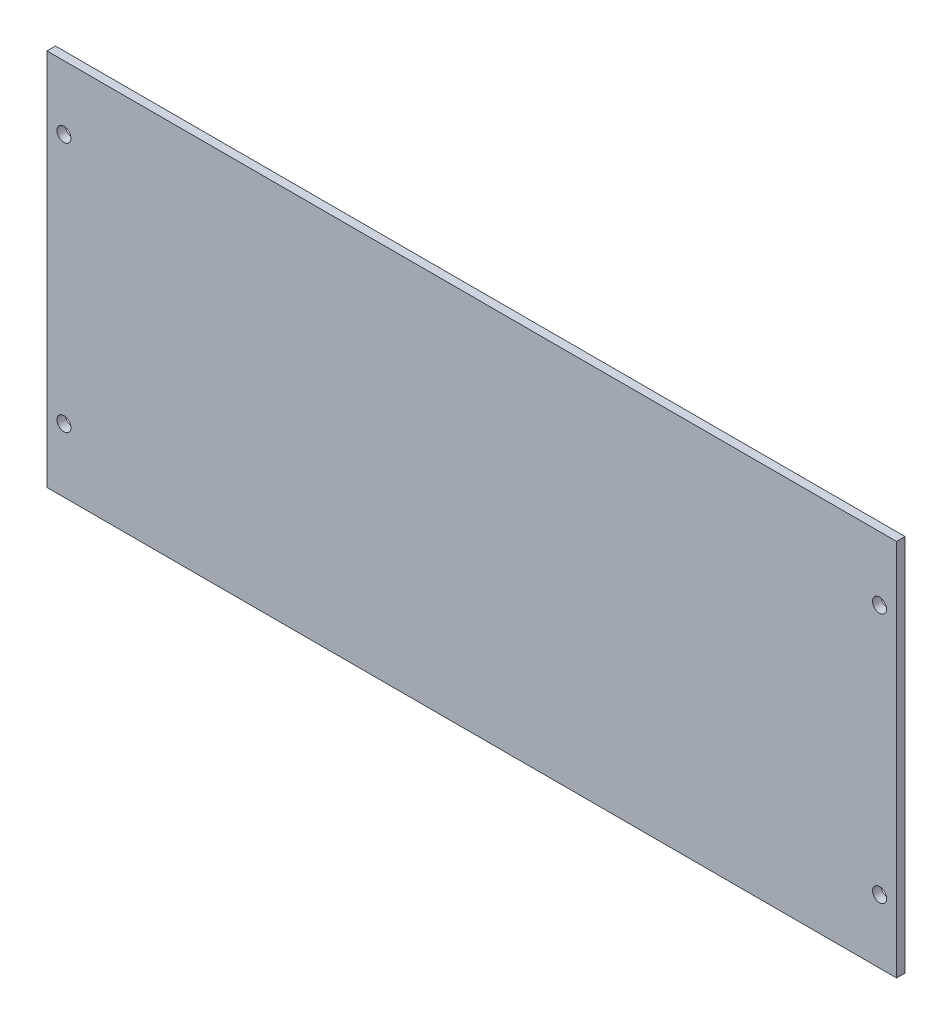
SolidWorks part; units mm, degrees
ref_plane "Plan de face" through (0, 0, 0) normal (0, 0, 1) x (1, 0, 0)
ref_plane "Plan de dessus" through (0, 0, 0) normal (0, 1, 0) x (1, 0, 0)
ref_plane "Plan de droite" through (0, 0, 0) normal (1, 0, 0) x (0, 0, -1)
sketch "Esquisse1" plane through (0, 0, 0) normal (0, 0, 1) x (1, 0, 0)
  line L1 (-200, -89) -> (200, -89)
  line L2 (-200, -89) -> (-200, 89)
  line L3 (-200, 89) -> (200, 89)
  line L4 (200, -89) -> (200, 89)
  line L5 (-200, -89) -> (200, 89) construction
  line L6 (-200, 89) -> (200, -89) construction
  point P0 (0, 0)
  dimension "D1" = 178
  dimension "D2" = 400
extrude "Boss.-Extru.1" add sketch "Esquisse1" along normal blind 4
sketch "Esquisse2" plane through (0, 0, 0) normal (0, 0, -1) x (-1, 0, 0)
  line L0 (200, -89) -> (-200, -89) construction
  line L1 (192, -81) -> (-192, -81) construction
  line L2 (192, -81) -> (192, 81) construction
  line L3 (192, 81) -> (-192, 81) construction
  line L4 (-192, -81) -> (-192, 81) construction
  line L5 (192, -81) -> (-192, 81) construction
  line L6 (192, 81) -> (-192, -81) construction
  line L7 (-200, -89) -> (-200, 89) construction
  line L8 (-153.9304, 0) -> (204.6118, 0) construction
  line L9 (0, -141.2759) -> (0, 199.6584) construction
  point P0 (0, 0)
  point P14 (-192, -59)
  point P15 (-192, 59)
  point P16 (192, -59)
  point P17 (192, 59)
  point P18 (0, 81)
  dimension "D1" = 8
  dimension "D2" = 8
  dimension "D3" = 30
hole_wizard "Dégagement M61" positions "Esquisse3D1" profile "Esquisse3" hole size "M6" standard "ISO" end condition through all
sketch3d "Esquisse3D1"
  point P3 (-192, 59, 0)
  point P6 (-192, -59, 0)
  point P9 (192, -59, 0)
  point P12 (192, 59, 0)
sketch "Esquisse3" plane through (-192, 59, 0) normal (1, 0, 0) x (0, 1, 0)
  line L0 (0, 0) -> (0, 4)
  line L1 (0, 4) -> (3.3, 4)
  line L2 (3.3, 4) -> (3.3, 0)
  line L5 (3.3, 0) -> (0, 0)
  line L11 (0, -6.35) -> (0, 107.95) construction
  dimension "Diamètre du perçage jusqu'au prochain" = 6.6
  dimension "Profondeur du perçage jusqu'au prochain" = 4
